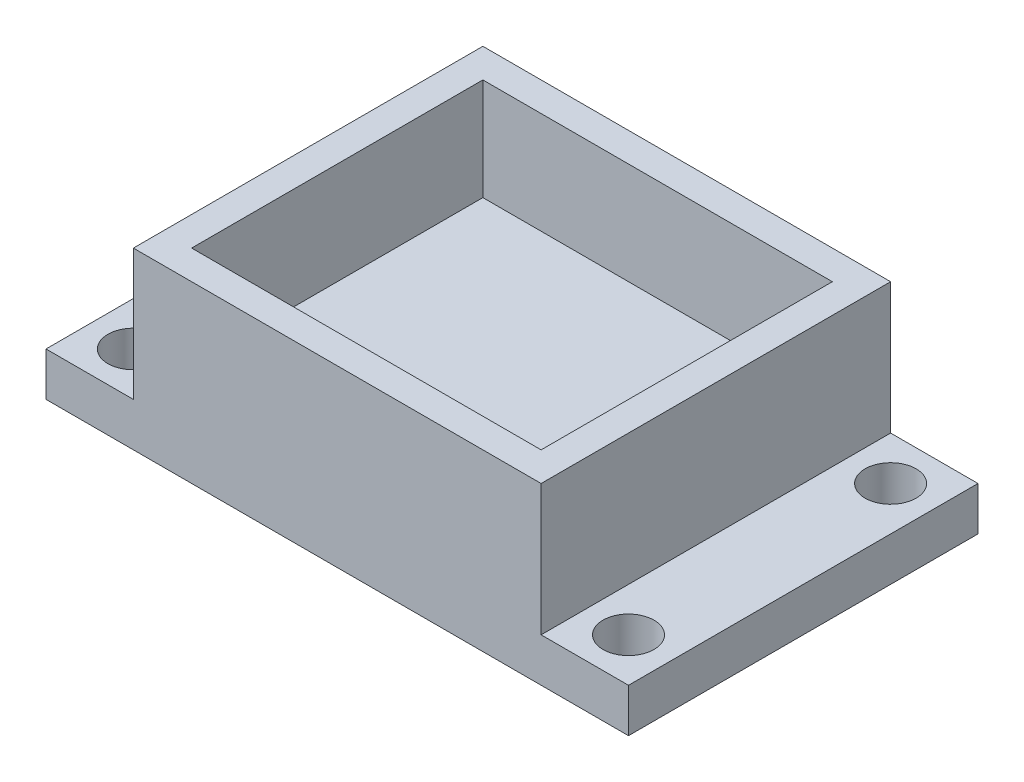
SolidWorks part; units mm, degrees
ref_plane "前视基准面" through (0, 0, 0) normal (0, 0, 1) x (1, 0, 0)
ref_plane "上视基准面" through (0, 0, 0) normal (0, 1, 0) x (1, 0, 0)
ref_plane "右视基准面" through (0, 0, 0) normal (1, 0, 0) x (0, 0, -1)
sketch "草图1" plane through (0, 0, 0) normal (0, 1, 0) x (1, 0, 0)
  line L1 (-14, 12) -> (14, 12)
  line L2 (-14, 12) -> (-14, -12)
  line L3 (-14, -12) -> (14, -12)
  line L4 (14, 12) -> (14, -12)
  line L5 (-14, 12) -> (14, -12) construction
  line L6 (-14, -12) -> (14, 12) construction
  point P0 (0, 0)
  dimension "D1" = 28
  dimension "D2" = 24
extrude "凸台-拉伸2" add sketch "草图1" along normal blind 12
sketch "草图2" plane through (0, 12, 0) normal (0, 1, 0) x (1, 0, 0)
  line L1 (-12, 10) -> (12, 10)
  line L2 (-12, 10) -> (-12, -10)
  line L3 (-12, -10) -> (12, -10)
  line L4 (12, 10) -> (12, -10)
  line L5 (-12, 10) -> (12, -10) construction
  line L6 (-12, -10) -> (12, 10) construction
  point P0 (0, 0)
  dimension "D1" = 24
  dimension "D2" = 20
extrude "切除-拉伸1" cut sketch "草图2" against normal blind 7
ref_plane "基准面4" through (0, 0, 0) normal (-1, 0, 0) x (0, 0, 1)
sketch "草图3" plane through (-14, 0, 0) normal (-1, 0, 0) x (0, 0, 1)
  line L0 (12, 12) -> (12, 0) construction
  line L1 (-12, 0) -> (12, 0)
  line L2 (-12, 0) -> (-12, 3)
  line L3 (-12, 3) -> (12, 3)
  line L4 (12, 0) -> (12, 3)
  dimension "D1" = 3
extrude "凸台-拉伸4" add sketch "草图3" along normal blind 6
sketch "草图4" plane through (0, 3, 0) normal (0, 1, 0) x (1, 0, 0)
  line L0 (-20, -12) -> (-14, -12) construction
  line L1 (-20, -12) -> (-20, 12) construction
  line L2 (-20, 12) -> (-14, 12) construction
  point P0 (-17, 9)
  point P1 (-17, -9)
  dimension "D1" = 3
  dimension "D2" = 3
  dimension "D3" = 3
  dimension "D4" = 3
sketch "草图5" plane through (0, 3, 0) normal (0, 1, 0) x (1, 0, 0)
  point P0 (-17, 9)
  point P3 (-17, -9)
hole_wizard "孔1" positions "草图5" profile "草图6" legacy end condition up to next
sketch "草图6" plane through (-17, 3, -9) normal (1, 0, 0) x (0, 0, 1)
  line L0 (0, 0) -> (0, 3)
  line L1 (0, 3) -> (1.75, 3)
  line L2 (1.75, 3) -> (1.75, 0)
  line L3 (1.75, 0) -> (0, 0)
  line L4 (0, 110) -> (0, -10) construction
  dimension "直径" = 3.5
  dimension "深度" = 3
mirror "镜向1" about plane through (0, 0, 0) normal (-1, 0, 0) of "凸台-拉伸4", "孔1"
sketch "草图7" plane through (0, 5, 0) normal (0, 1, 0) x (1, 0, 0)
  line L0 (9.5, 7.5) -> (9.5, -7.5)
  line L1 (-11.5, -9.5) -> (11.5, -9.5)
  line L2 (-11.5, -9.5) -> (-11.5, 9.5)
  line L3 (-11.5, 9.5) -> (11.5, 9.5)
  line L4 (11.5, -9.5) -> (11.5, 9.5)
  line L5 (-11.5, -9.5) -> (11.5, 9.5) construction
  line L6 (-11.5, 9.5) -> (11.5, -9.5) construction
  line L8 (9.5, 3.5) -> (11.5, 3.5)
  line L9 (9.5, 3.5) -> (9.5, -3.5)
  line L10 (9.5, -3.5) -> (11.5, -3.5)
  line L11 (11.5, 3.5) -> (11.5, -3.5)
  point P0 (0, 0)
  point P6 (9.5, -7.5)
  point P7 (9.5, 7.5)
  dimension "D1" = 23
  dimension "D2" = 19
  dimension "D3" = 2
  dimension "D4" = 2
  dimension "D5" = 2
  dimension "D6" = 2
  dimension "D7" = 4
  dimension "D8" = 4
  dimension "D9" = 2
sketch "草图8" plane through (0, 5, 0) normal (0, 1, 0) x (1, 0, 0)
  point P0 (9.5, 7.5)
  point P3 (9.5, -7.5)
hole_wizard "孔2" positions "草图8" profile "草图9" legacy end condition up to next
sketch "草图9" plane through (9.5, 5, -7.5) normal (1, 0, 0) x (0, 0, 1)
  line L0 (0, 0) -> (0, 5)
  line L1 (0, 5) -> (1.15, 5)
  line L2 (1.15, 5) -> (1.15, 0)
  line L3 (1.15, 0) -> (0, 0)
  line L4 (0, 110) -> (0, -10) construction
  dimension "直径" = 2.3
  dimension "深度" = 5
sketch "草图10" plane through (0, 5, 0) normal (0, 1, 0) x (1, 0, 0)
  line L0 (12, -10) -> (12, 10) construction
  line L1 (9.5, 3.5) -> (12, 3.5)
  line L2 (9.5, 3.5) -> (9.5, -3.5)
  line L3 (9.5, -3.5) -> (12, -3.5)
  line L4 (12, 3.5) -> (12, -3.5)
  dimension "D1" = 7
extrude "切除-拉伸2" cut sketch "草图10" against normal blind 1
sketch "草图11" plane through (0, 0, 0) normal (0, -1, 0) x (-1, 0, 0)
  line L1 (-11.9249, -7.5) -> (-10.7124, -9.6)
  line L2 (-10.7124, -9.6) -> (-8.2876, -9.6)
  line L3 (-8.2876, -9.6) -> (-7.0751, -7.5)
  line L4 (-7.0751, -7.5) -> (-8.2876, -5.4)
  line L5 (-8.2876, -5.4) -> (-10.7124, -5.4)
  line L6 (-10.7124, -5.4) -> (-11.9249, -7.5)
  line L7 (-11.9249, 7.5) -> (-10.7124, 5.4)
  line L8 (-10.7124, 5.4) -> (-8.2876, 5.4)
  line L9 (-8.2876, 5.4) -> (-7.0751, 7.5)
  line L10 (-7.0751, 7.5) -> (-8.2876, 9.6)
  line L11 (-8.2876, 9.6) -> (-10.7124, 9.6)
  line L12 (-10.7124, 9.6) -> (-11.9249, 7.5)
  circle A0 centre (-9.5, -7.5) radius 2.1 construction
  circle A1 centre (-9.5, 7.5) radius 2.1 construction
  dimension "D1" = 4.2
  dimension "D2" = 4.2
extrude "切除-拉伸3" cut sketch "草图11" against normal blind 3.2
